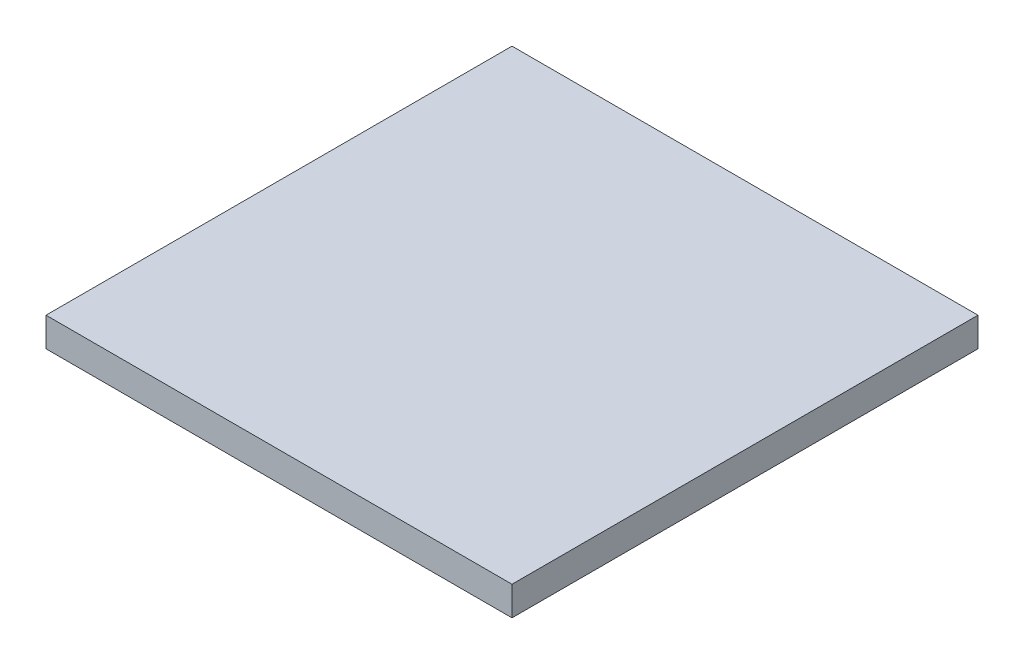
SolidWorks part; units mm, degrees
ref_plane "Front Plane" through (0, 0, 0) normal (0, 0, 1) x (1, 0, 0)
ref_plane "Top Plane" through (0, 0, 0) normal (0, 1, 0) x (1, 0, 0)
ref_plane "Right Plane" through (0, 0, 0) normal (1, 0, 0) x (0, 0, -1)
sketch "Sketch1" plane through (0, 0, 0) normal (0, 1, 0) x (1, 0, 0)
  line L1 (0.7527, 0.0112) -> (-24.6473, 0.0112)
  line L2 (0.7527, 0.0112) -> (0.7527, 25.4112)
  line L3 (0.7527, 25.4112) -> (-24.6473, 25.4112)
  line L4 (-24.6473, 0.0112) -> (-24.6473, 25.4112)
  dimension "D1" = 25.4
  dimension "D2" = 25.4
extrude "Boss-Extrude1" add sketch "Sketch1" along normal blind 1.5875
sketch "Sketch2" plane through (0, 0, 0) normal (0, -1, 0) x (-1, 0, 0)
  line L0 (17.955, 12.7112) -> (5.9396, 12.7112)
  line L1 (5.9396, 12.7112) -> (4.8861, 15.7592)
  line L2 (4.8861, 15.7592) -> (4.8861, 25.4112)
  line L3 (4.8861, 25.4112) -> (19.0085, 25.4112)
  line L4 (19.0085, 25.4112) -> (19.0085, 15.7592)
  line L5 (19.0085, 15.7592) -> (17.955, 12.7112)
  line L6 (-0.7527, 25.4112) -> (24.6473, 25.4112) construction
  line L7 (24.6473, 25.4112) -> (24.6473, 0.0112) construction
  line L8 (-0.7527, 0.0112) -> (-0.7527, 25.4112) construction
  point P12 (11.9473, 25.4112)
  point P13 (11.9473, 12.7112)
  dimension "D1" = 19.7612
  dimension "D2" = 19.7612
  dimension "D3" = 12.7
  dimension "D4" = 9.652
extrude "Boss-Extrude2" add sketch "Sketch2" along normal blind 3.302
